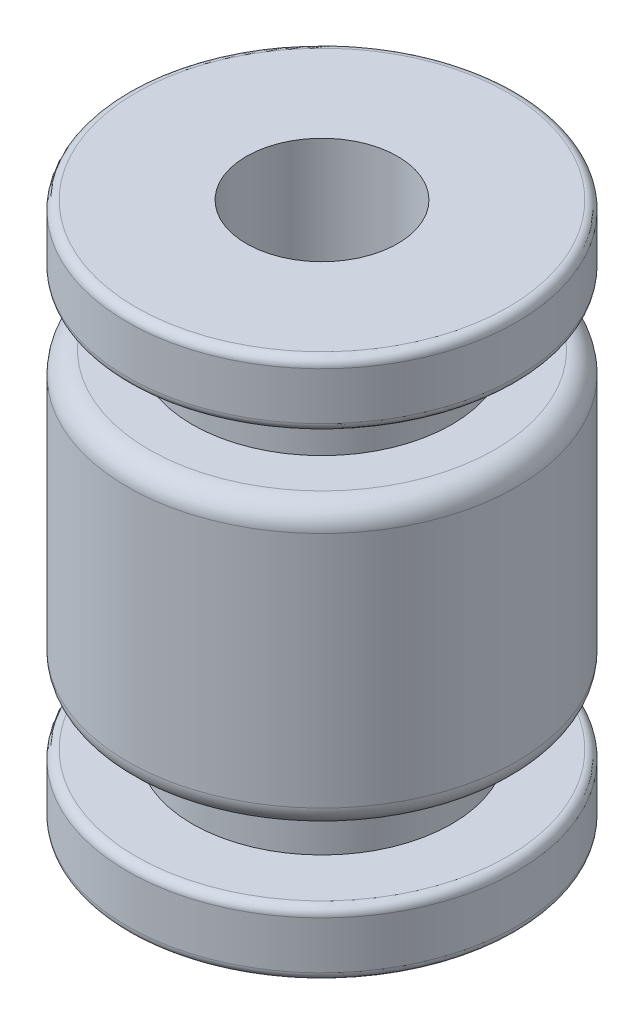
SolidWorks part; units mm, degrees
ref_plane "Front Plane" through (0, 0, 0) normal (0, 0, 1) x (1, 0, 0)
ref_plane "Top Plane" through (0, 0, 0) normal (0, 1, 0) x (1, 0, 0)
ref_plane "Right Plane" through (0, 0, 0) normal (1, 0, 0) x (0, 0, -1)
sketch "Sketch1" plane through (0, 0, 0) normal (0, 0, 1) x (1, 0, 0)
  line L0 (0, 6.25) -> (0, -6.25) construction
  line L1 (1.75, 6.25) -> (1.75, -6.25)
  line L2 (1.75, -6.25) -> (4.5, -6.25)
  line L3 (4.5, -6.25) -> (4.5, -4.75)
  line L4 (4.5, -4.75) -> (3, -4.75)
  line L5 (3, -4.75) -> (3, -3.25)
  line L6 (3, -3.25) -> (4.5, -3.25)
  line L7 (4.5, -3.25) -> (4.5, 3.25)
  line L8 (4.5, 3.25) -> (3, 3.25)
  line L9 (3, 3.25) -> (3, 4.75)
  line L10 (3, 4.75) -> (4.5, 4.75)
  line L11 (4.5, 4.75) -> (4.5, 6.25)
  line L12 (4.5, 6.25) -> (1.75, 6.25)
  point P2 (0, 0)
  point P3 (1.75, 0)
  dimension "D1" = 1.5
  dimension "D2" = 6.5
  dimension "D3" = 9
  dimension "D4" = 3.5
revolve "Revolve1" add sketch "Sketch1" angle 360 about L0
fillet "Fillet1" radius 0.5 2 edges at (-4.5, -3.25, 0) (-4.5, 3.25, 0)
fillet "Fillet2" radius 0.2 4 edges at (-4.5, -6.25, 0) (-4.5, -4.75, 0) (-4.5, 4.75, 0) (-4.5, 6.25, 0)
